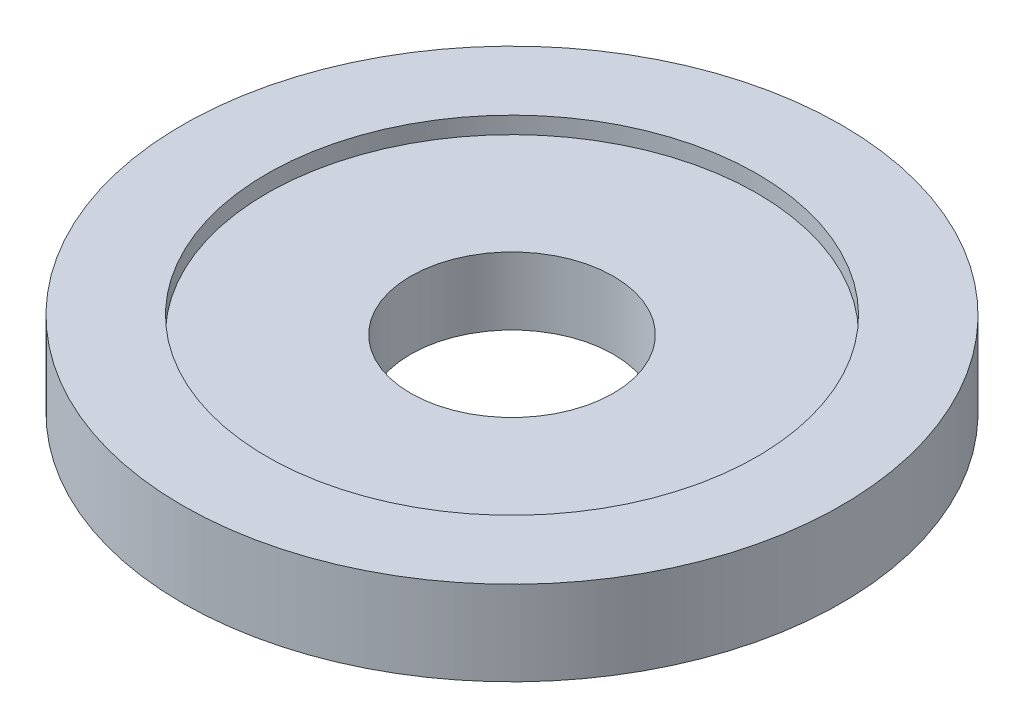
SolidWorks part; units mm, degrees
material "Delrin 2700 NC010, Low Viscosity Acetal Copolymer (SS)"
ref_plane "Front Plane" through (0, 0, 0) normal (0, 0, 1) x (1, 0, 0)
ref_plane "Top Plane" through (0, 0, 0) normal (0, 1, 0) x (1, 0, 0)
ref_plane "Right Plane" through (0, 0, 0) normal (1, 0, 0) x (0, 0, -1)
sketch "Sketch1" plane through (0, 0, 0) normal (0, 0, 1) x (1, 0, 0)
  line L0 (0, 0) -> (0, 41.8565) construction
  line L1 (0, 0) -> (12, 0) construction
  line L2 (12, 0) -> (12, 8)
  line L3 (12, 8) -> (29, 8)
  line L8 (29, 8) -> (29, 10)
  line L9 (29, 10) -> (39, 10)
  line L10 (39, 10) -> (39, 0)
  line L11 (39, 0) -> (12, 0)
  dimension "D1" = 8
  dimension "D2" = 29
  dimension "D3" = 39
  dimension "D4" = 10
  dimension "D5" = 12
revolve "Revolve1" add sketch "Sketch1" angle 360 about L0
